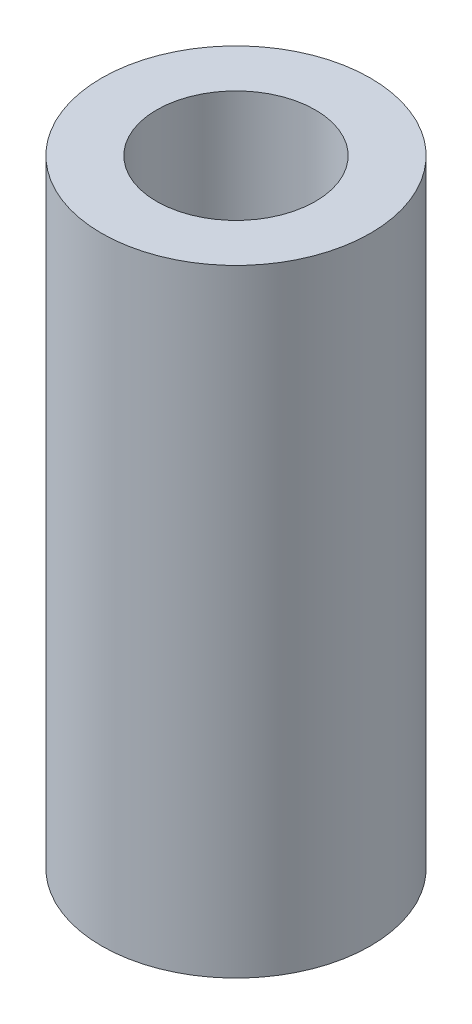
SolidWorks part; units mm, degrees
ref_plane "Alzado" through (0, 0, 0) normal (0, 0, 1) x (1, 0, 0)
ref_plane "Planta" through (0, 0, 0) normal (0, 1, 0) x (1, 0, 0)
ref_plane "Vista lateral" through (0, 0, 0) normal (1, 0, 0) x (0, 0, -1)
sketch "Croquis base" plane through (0, 0, 0) normal (0, 1, 0) x (1, 0, 0)
  circle A0 centre (0, 0) radius 1.525
  circle A2 centre (0, 0) radius 0.9
extrude "Saliente-Extruir1" add sketch "Croquis base" along normal blind 7
